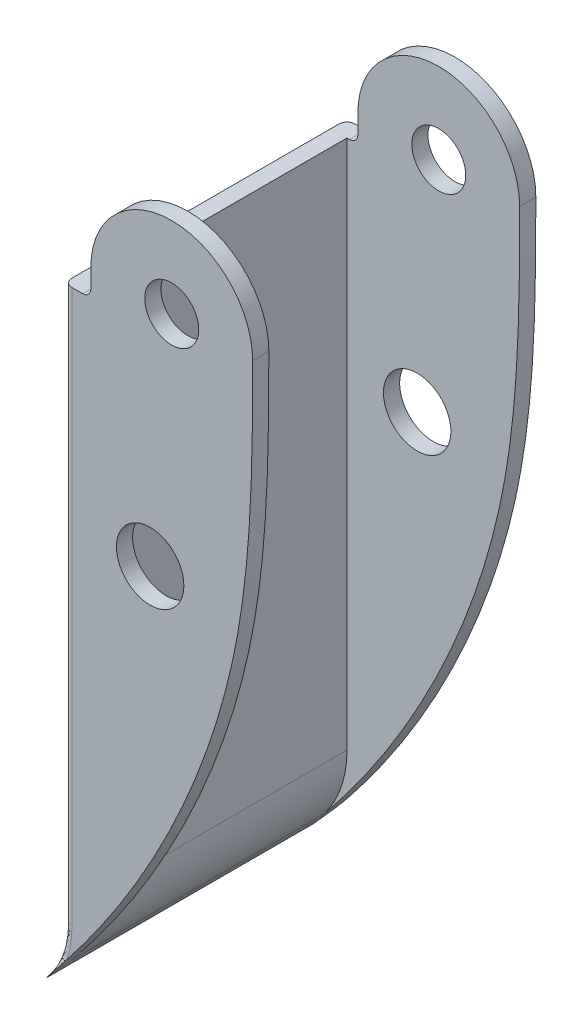
SolidWorks part; units mm, degrees
material "合金钢"
ref_plane "前视基准面" through (0, 0, 0) normal (0, 0, 1) x (1, 0, 0)
ref_plane "上视基准面" through (0, 0, 0) normal (0, 1, 0) x (1, 0, 0)
ref_plane "右视基准面" through (0, 0, 0) normal (1, 0, 0) x (0, 0, -1)
sketch "草图1" plane through (0, 0, 0) normal (0, 0, 1) x (1, 0, 0)
  line L0 (1, 0) -> (1, -1)
  line L1 (1, -1) -> (0, -1)
  line L2 (0, -1) -> (0, -21.5)
  circle A0 centre (4, 0) radius 1
  arc A1 (7, 0) -> (1, 0) centre (4, 0) ccw
  spline S0 degree 3 poles (7, 0) (7, -3.4618) (6.8882, -11.8436) (2.5115, -20.0309) (-1, -24) knots 0 0 0 0 0.379768 1 1 1 1
  spline S1 degree 2 poles (0, -21.5) (0, -22.8834) (-1, -24) knots 0 0 0 1 1 1
  dimension "D1" = 2
  dimension "D2" = 6
  dimension "D3" = 4
  dimension "D4" = 1
  dimension "D5" = 20.5
  dimension "D6" = 1
  dimension "D7" = 1
  dimension "D8" = 2.5
  dimension "D9" = 9.8
  dimension "D10" = 6.3
extrude "凸台-拉伸1" add sketch "草图1" along normal blind 10.5 contours L2 S1 S0 A1 L0 L1 A0
ref_plane "基准面1" through (0.6, 0, 0) normal (-1, 0, 0) x (0, 0, 1)
sketch "草图2" plane through (0.6, 0, 0) normal (-1, 0, 0) x (0, 0, 1)
  line L0 (10.5, -1) -> (10.5, -21.5) construction
  line L1 (0.6, 3.0518) -> (9.9, 3.0518)
  line L2 (0.6, 3.0518) -> (0.6, -23.9482)
  line L3 (0.6, -23.9482) -> (9.9, -23.9482)
  line L4 (9.9, 3.0518) -> (9.9, -23.9482)
  line L5 (0, -21.5) -> (0, -23.9482) construction
  line L7 (10.5, -23.9482) -> (0, -23.9482) construction
  dimension "D1" = 0.6
  dimension "D2" = 0.6
  dimension "D3" = 27
extrude "切除-拉伸1" cut sketch "草图2" against normal blind 10.5
fillet "圆角1" radius 4 1 edges at (0.6, -22.0416, 5.25)
fillet "圆角2" radius 0.3 6 edges at (1, -1, 0.3) (0, -11.25, 10.5) (0, -11.25, 0) (1, -1, 10.2)
sketch "草图3" plane through (0, 0, 0) normal (0, 0, -1) x (-1, 0, 0)
  circle A0 centre (-3.2, -8.5) radius 1.25
  circle A1 centre (-4, 0) radius 1 construction
  dimension "D1" = 2.5
  dimension "D2" = 8.5
  dimension "D3" = 0.8
extrude "切除-拉伸2" cut sketch "草图3" against normal blind 19
